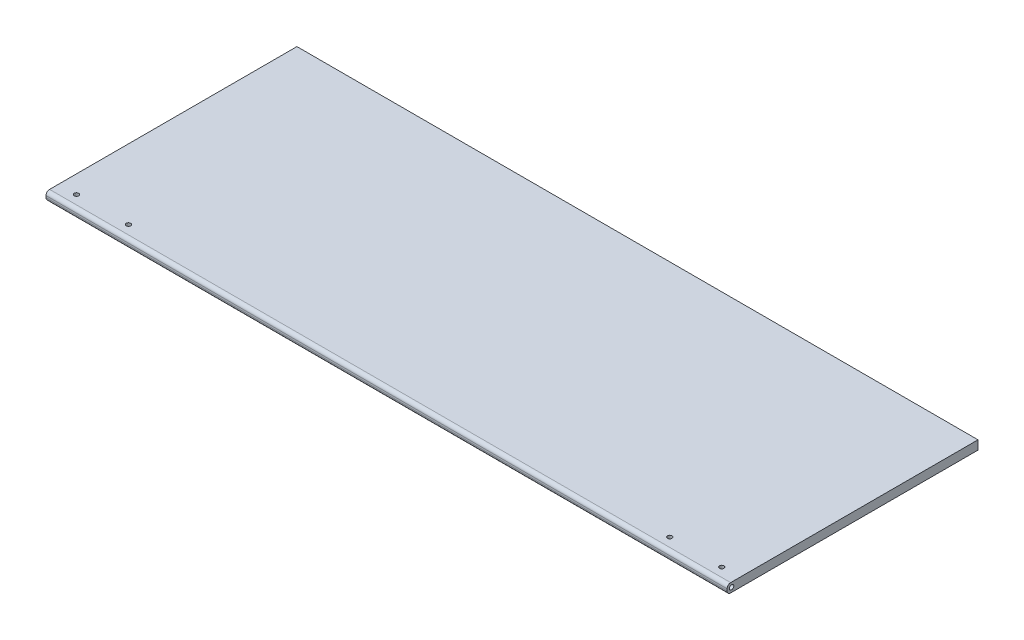
SolidWorks part; units mm, degrees
ref_plane "Front Plane" through (0, 0, 0) normal (0, 0, 1) x (1, 0, 0)
ref_plane "Top Plane" through (0, 0, 0) normal (0, 1, 0) x (1, 0, 0)
ref_plane "Right Plane" through (0, 0, 0) normal (1, 0, 0) x (0, 0, -1)
sketch "Sketch1" plane through (0, 0, 0) normal (0, 1, 0) x (1, 0, 0)
  line L1 (-241.3, 88.9) -> (241.3, 88.9)
  line L2 (-241.3, 88.9) -> (-241.3, -88.9)
  line L3 (-241.3, -88.9) -> (241.3, -88.9)
  line L4 (241.3, 88.9) -> (241.3, -88.9)
  line L5 (-241.3, 88.9) -> (241.3, -88.9) construction
  line L6 (-241.3, -88.9) -> (241.3, 88.9) construction
  point P0 (0, 0)
  dimension "D1" = 177.8
  dimension "D2" = 482.6
extrude "Boss-Extrude1" add sketch "Sketch1" along normal blind 6.35
sketch "Sketch2" plane through (-241.3, 0, 0) normal (-1, 0, 0) x (0, 0, 1)
  line L0 (-88.9, 6.35) -> (88.9, 6.35) construction
  line L1 (88.9, 6.35) -> (88.9, 0) construction
  circle A0 centre (85.725, 3.175) radius 1.5875
  dimension "D1" = 3.175
  dimension "D2" = 3.175
  dimension "D3" = 3.175
extrude "Cut-Extrude1" cut sketch "Sketch2" against normal through all
fillet "Fillet1" radius 2.54 2 edges at (0, 0, 88.9) (0, 6.35, 88.9)
sketch "Sketch4" plane through (0, 0, 0) normal (0, -1, 0) x (1, 0, 0)
  line L0 (241.3, 86.36) -> (-241.3, 86.36) construction
  line L1 (-241.3, -88.9) -> (-241.3, 86.36) construction
  circle A0 centre (-191.77, 80.01) radius 1.5875
  circle A1 centre (-228.6, 80.01) radius 1.5875
  dimension "D2" = 3.175
  dimension "D1" = 6.35
  dimension "D3" = 36.83
  dimension "D4" = 12.7
extrude "Cut-Extrude3" cut sketch "Sketch4" against normal through all
mirror "Mirror1" about plane through (0, 0, 0) normal (1, 0, 0) of "Cut-Extrude3"
scale "Scale1" scale about centroid uniform scaling yes scale factor 0.25
